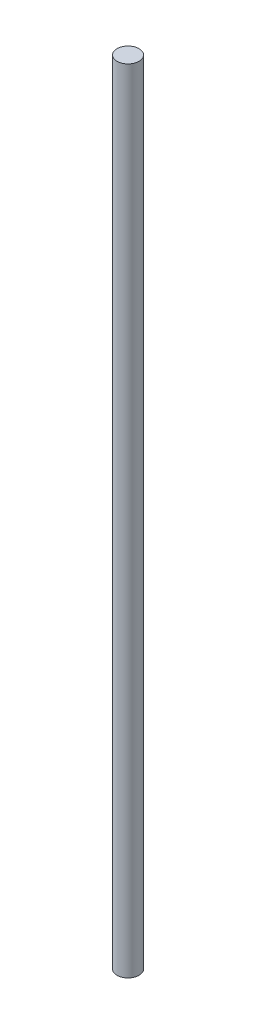
SolidWorks part; units mm, degrees
ref_plane "Спереди" through (0, 0, 0) normal (0, 0, 1) x (1, 0, 0)
ref_plane "Сверху" through (0, 0, 0) normal (0, 1, 0) x (1, 0, 0)
ref_plane "Справа" through (0, 0, 0) normal (1, 0, 0) x (0, 0, -1)
sketch "Эскиз1" plane through (0, 0, 0) normal (0, 1, 0) x (1, 0, 0)
  circle A0 centre (0, 0) radius 2.5
  dimension "D1" = 5
extrude "Бобышка-Вытянуть1" add sketch "Эскиз1" along normal blind 180
equation "\"motor_diameter\"= 30"
equation "\"mm_diameter\"= IIF ( \"motor_diameter\" < 34 , 41 , \"motor_diameter\" + 8 )"
equation "\"upper_shafts_diameter\"= 5"
equation "\"upper_shats_length\"= 180"
equation "\"upper_bearing_d1\"= 10"
equation "\"upper_bearing_d2\"= 5"
equation "\"upper_bearing_h\"= 15"
equation "\"lower_shafts_diameter\"= 5"
equation "\"lower_shafts_length\"= 180"
equation "\"lower_bearing_d1\"= 10"
equation "\"lower_bearing_d2\"= 5"
equation "\"lower_bearing_h\"= 15"
equation "\"print_offset\"= 0.5"
equation "\"bh_screws_d\"= 2"
equation "\"bh_screws_h\"= 20"
equation "\"bh_screws_hh_d\"= 3.4"
equation "\"bh_screws_hh_h\"= 2"
equation "\"bh_nut_d\"= 3.8"
equation "\"bh_nut_h\"= 2"
equation "\"motor_screws_d\"= 3"
equation "\"motor_screws_h\"= 16"
equation "\"motor_screws_hh_d\"= 5.5"
equation "\"motor_screws_hh_h\"= 3"
equation "\"plate_hole_distance\"= 25.4"
equation "\"plate_screws_d\"= 6.5"
equation "\"D1@Эскиз1\"=\"lower_shafts_diameter\""
equation "\"D1@Бобышка-Вытянуть1\"=\"lower_shafts_length\""
